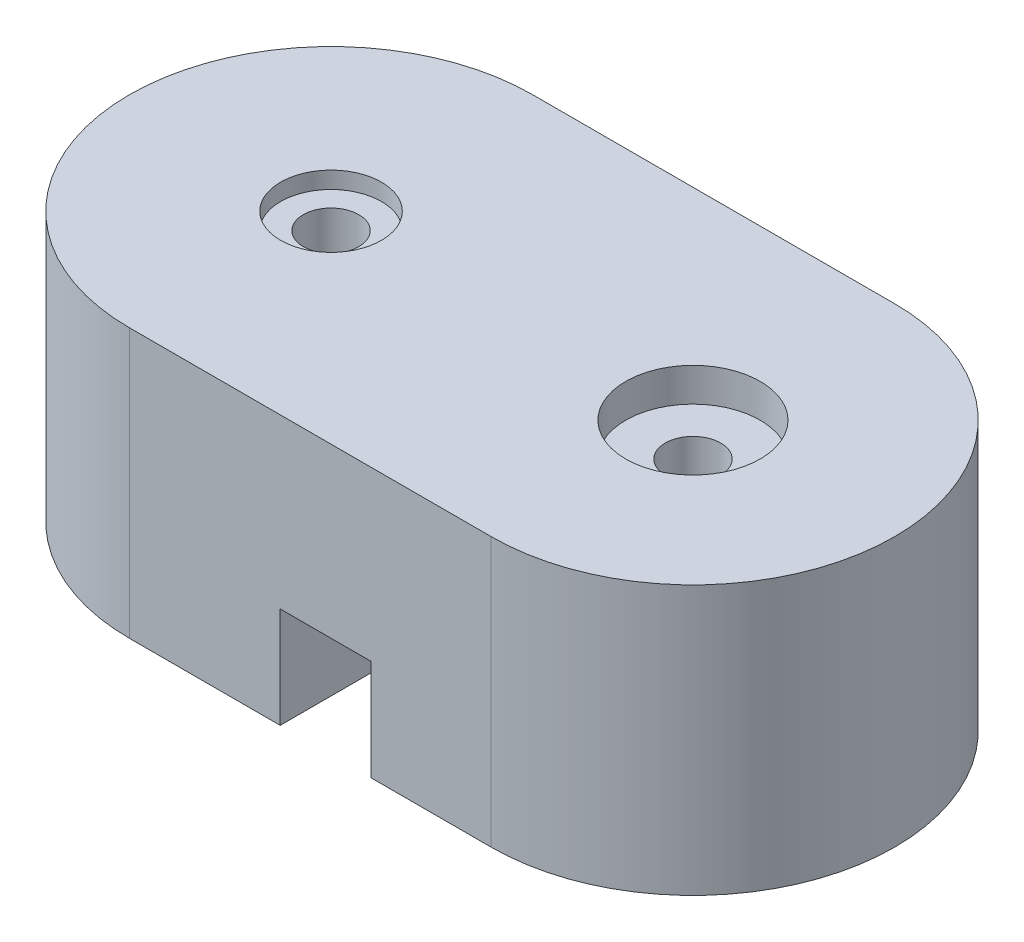
SolidWorks part; units mm, degrees
ref_plane "前视基准面" through (0, 0, 0) normal (0, 0, 1) x (1, 0, 0)
ref_plane "上视基准面" through (0, 0, 0) normal (0, 1, 0) x (1, 0, 0)
ref_plane "右视基准面" through (0, 0, 0) normal (1, 0, 0) x (0, 0, -1)
other "Configuration Table"
sketch "草图1" plane through (0, 0, 0) normal (0, 1, 0) x (1, 0, 0)
  line L0 (-10.765, 0) -> (10.765, 0) construction
  line L1 (-10.765, 12) -> (10.765, 12)
  line L2 (-10.765, -12) -> (10.765, -12)
  arc A0 (-10.765, 12) -> (-10.765, -12) centre (-10.765, 0) ccw
  arc A1 (10.765, -12) -> (10.765, 12) centre (10.765, 0) ccw
  point P2 (0, 0)
  dimension "D2" = 12
  dimension "D1" = 21.53
extrude "凸台-拉伸1" add sketch "草图1" along normal blind 13
sketch "草图2" plane through (0, 0, 0) normal (0, -1, 0) x (1, 0, 0)
  line L0 (0, 0) -> (0, 12) construction
  line L1 (-10.765, 12) -> (10.765, 12) construction
  line L2 (0, 12) -> (-1.79, 12)
  line L3 (0, 12) -> (3.6, 12)
  line L4 (-1.79, 12) -> (-1.79, -12)
  line L5 (10.765, -12) -> (-10.765, -12) construction
  line L6 (-1.79, -12) -> (3.6, -12)
  line L7 (3.6, -12) -> (3.6, 12)
  dimension "D3" = 1.79
  dimension "D4" = 3.6
extrude "切除-拉伸1" cut sketch "草图2" against normal blind 3
sketch "草图3" plane through (0, 13, 0) normal (0, 1, 0) x (1, 0, 0)
  circle A0 centre (10.765, 0) radius 4
  dimension "D1" = 8
extrude "切除-拉伸2" cut sketch "草图3" against normal blind 2
sketch "草图4" plane through (0, 11, 0) normal (0, 1, 0) x (1, 0, 0)
  circle A0 centre (10.765, 0) radius 1.65
  dimension "D1" = 3.3
extrude "切除-拉伸3" cut sketch "草图4" against normal through all
sketch "草图5" plane through (0, 13, 0) normal (0, 1, 0) x (1, 0, 0)
  circle A0 centre (-10.765, 0) radius 3
  dimension "D1" = 6
extrude "切除-拉伸4" cut sketch "草图5" against normal blind 1
sketch "草图6" plane through (0, 12, 0) normal (0, 1, 0) x (1, 0, 0)
  circle A0 centre (-10.765, 0) radius 1.65
  dimension "D1" = 3.3
extrude "切除-拉伸5" cut sketch "草图6" against normal through all
sketch "草图7" plane through (0, 0, 0) normal (0, -1, 0) x (1, 0, 0)
  circle A1 centre (10.765, 0) radius 7.5
  dimension "D2" = 15
extrude "切除-拉伸6" cut sketch "草图7" against normal blind 6.3
sketch "草图8" plane through (0, 0, 0) normal (0, -1, 0) x (1, 0, 0)
  circle A0 centre (-10.765, 0) radius 5
  dimension "D1" = 10
extrude "切除-拉伸7" cut sketch "草图8" against normal blind 8.3
sketch "草图9" plane through (0, 0, 0) normal (0, -1, 0) x (1, 0, 0)
  line L3 (-10.765, -12) -> (-1.79, -12)
  line L4 (-1.79, -12) -> (-1.79, 12)
  line L5 (-1.79, 12) -> (-10.765, 12)
  line L6 (-10.765, -12) -> (-1.79, -12)
  line L7 (-1.79, -12) -> (-1.79, 12)
  line L8 (-1.79, 12) -> (-10.765, 12)
  line L10 (3.6, 12) -> (3.6, 2.2165)
  line L11 (3.6, -2.2165) -> (3.6, -12)
  line L12 (3.6, -12) -> (10.765, -12)
  line L13 (10.765, 12) -> (3.6, 12)
  line L14 (3.6, 12) -> (3.6, 2.2165)
  line L15 (3.6, -2.2165) -> (3.6, -12)
  line L16 (3.6, -12) -> (10.765, -12)
  line L17 (10.765, 12) -> (3.6, 12)
  circle A0 centre (-10.765, 0) radius 5 construction
  arc A1 (-10.765, 12) -> (-10.765, -12) centre (-10.765, 0) ccw
  arc A2 (-10.765, 12) -> (-10.765, -12) centre (-10.765, 0) ccw
  circle A3 centre (-10.765, 0) radius 5
  arc A4 (3.6, -2.2165) -> (3.6, 2.2165) centre (10.765, 0) ccw
  arc A5 (10.765, -12) -> (10.765, 12) centre (10.765, 0) ccw
  arc A6 (3.6, -2.2165) -> (3.6, 2.2165) centre (10.765, 0) ccw
  arc A7 (10.765, -12) -> (10.765, 12) centre (10.765, 0) ccw
  dimension "D1" = 0
  dimension "D2" = 0
extrude "凸台-拉伸3" add sketch "草图9" along normal blind 3
